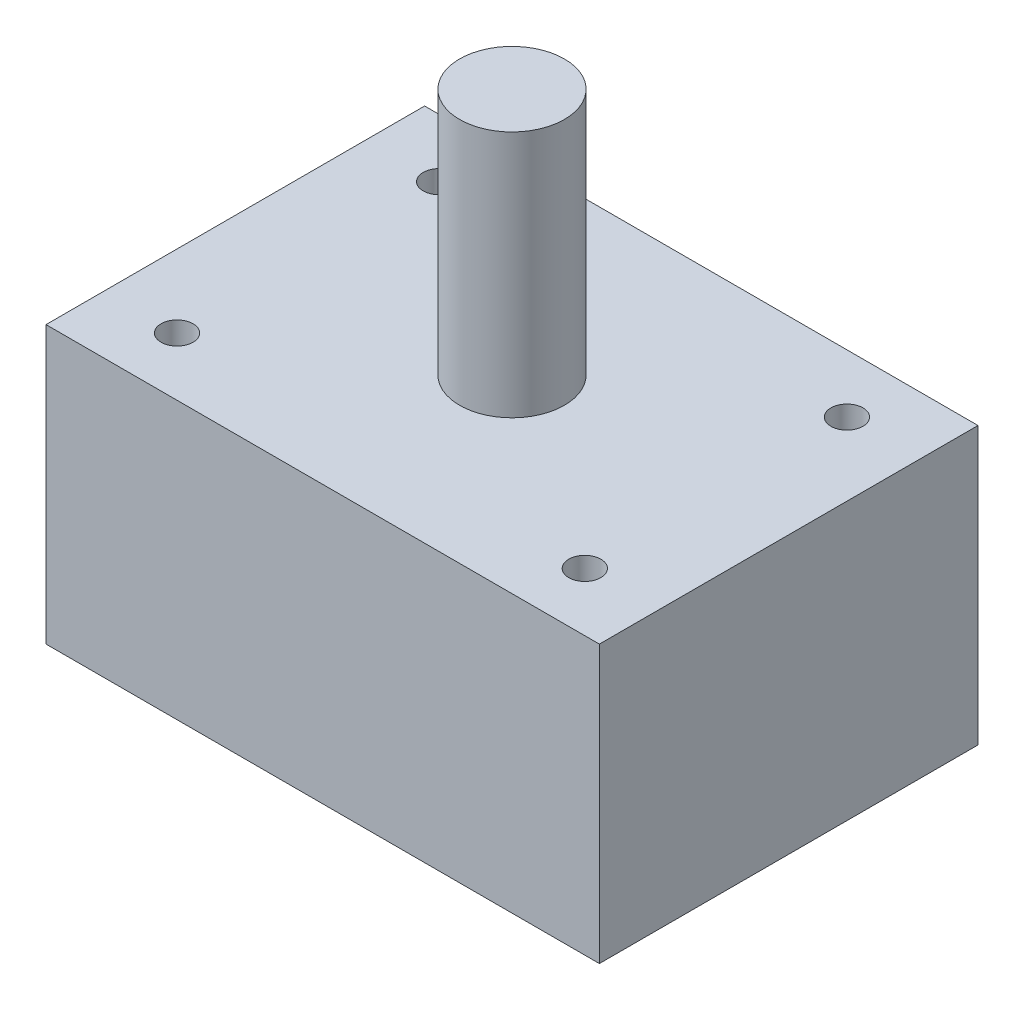
SolidWorks part; units mm, degrees
ref_plane "前视基准面" through (0, 0, 0) normal (0, 0, 1) x (1, 0, 0)
ref_plane "上视基准面" through (0, 0, 0) normal (0, 1, 0) x (1, 0, 0)
ref_plane "右视基准面" through (0, 0, 0) normal (1, 0, 0) x (0, 0, -1)
other "Configuration Table"
sketch "01_Housing_Profile" plane through (0, 0, 0) normal (0, 1, 0) x (1, 0, 0)
  line L1 (-95, -65) -> (95, -65)
  line L2 (-95, -65) -> (-95, 65)
  line L3 (-95, 65) -> (95, 65)
  line L4 (95, -65) -> (95, 65)
  line L5 (-95, -65) -> (95, 65) construction
  line L6 (-95, 65) -> (95, -65) construction
  circle A0 centre (-70, -45) radius 5.5
  circle A1 centre (70, -45) radius 5.5
  circle A2 centre (-70, 45) radius 5.5
  circle A3 centre (70, 45) radius 5.5
  point P0 (0, 0)
extrude "01_Housing_Block" add sketch "01_Housing_Profile" along normal blind 95
sketch "03_Output_Shaft_Profile" plane through (0, 0, 0) normal (0, 1, 0) x (1, 0, 0)
  circle A0 centre (0, 0) radius 18
extrude "03_Output_Shaft" add sketch "03_Output_Shaft_Profile" along normal blind 180
